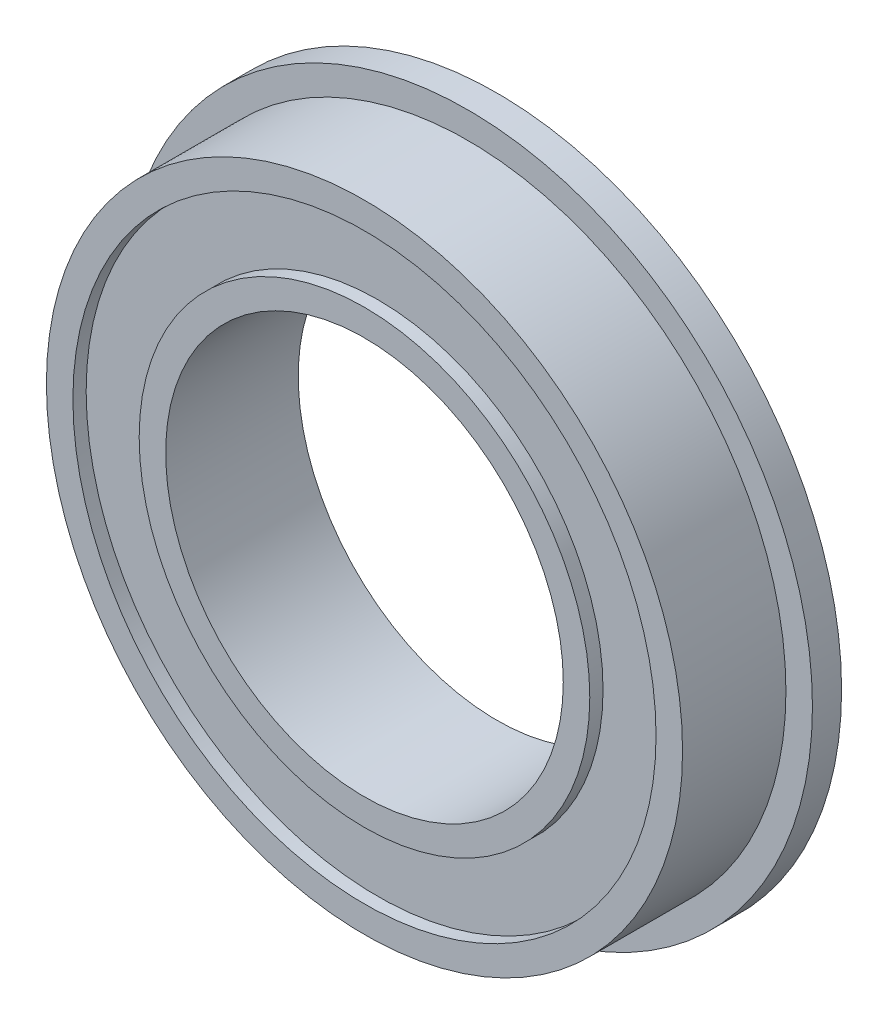
SolidWorks part; units mm, degrees
material "ｽﾃﾝﾚｽ鋼(ｸﾛﾑ)"
ref_plane "正面" through (0, 0, 0) normal (0, 0, 1) x (1, 0, 0)
ref_plane "平面" through (0, 0, 0) normal (0, 1, 0) x (1, 0, 0)
ref_plane "右側面" through (0, 0, 0) normal (1, 0, 0) x (0, 0, -1)
sketch "ｽｹｯﾁ1" plane through (0, 0, 0) normal (1, 0, 0) x (0, 0, -1)
  line L0 (0, 0) -> (0, 50000) construction
  line L1 (0, 0) -> (50000, 0) construction
  line L2 (0, 7.5) -> (5, 7.5)
  line L3 (5, 7.5) -> (5, 13)
  line L4 (5, 13) -> (3.9, 13)
  line L5 (3.9, 13) -> (3.9, 12)
  line L6 (3.9, 12) -> (0, 12)
  line L7 (0, 12) -> (0, 7.5)
  dimension "D1" = 15
  dimension "D2" = 24
  dimension "D3" = 26
  dimension "D4" = 1.1
  dimension "D5" = 5
revolve "回転1" add sketch "ｽｹｯﾁ1" angle 360 about L1
sketch "ｽｹｯﾁ2" plane through (0, 0, 0) normal (1, 0, 0) x (0, 0, -1)
  line L0 (0, 0) -> (50000, 0) construction
  line L1 (0, 12) -> (0, -12) construction
  line L3 (0, 11) -> (0.5, 11)
  line L4 (0, 11) -> (0, 8.5)
  line L5 (0, 8.5) -> (0.5, 8.5)
  line L7 (0.5, 11) -> (0.5, 8.5)
  line L8 (2.5, 14.8981) -> (2.5, -49985.1019) construction
  line L9 (5, -13) -> (5, 13) construction
  line L10 (4.5, 11) -> (4.5, 8.5)
  line L11 (5, 8.5) -> (4.5, 8.5)
  line L12 (5, 11) -> (5, 8.5)
  line L13 (5, 11) -> (4.5, 11)
  dimension "D1" = 17
  dimension "D2" = 22
  dimension "D3" = 0.5
revolve "ｶｯﾄ - 回転1" cut sketch "ｽｹｯﾁ2" angle 360 about L0
